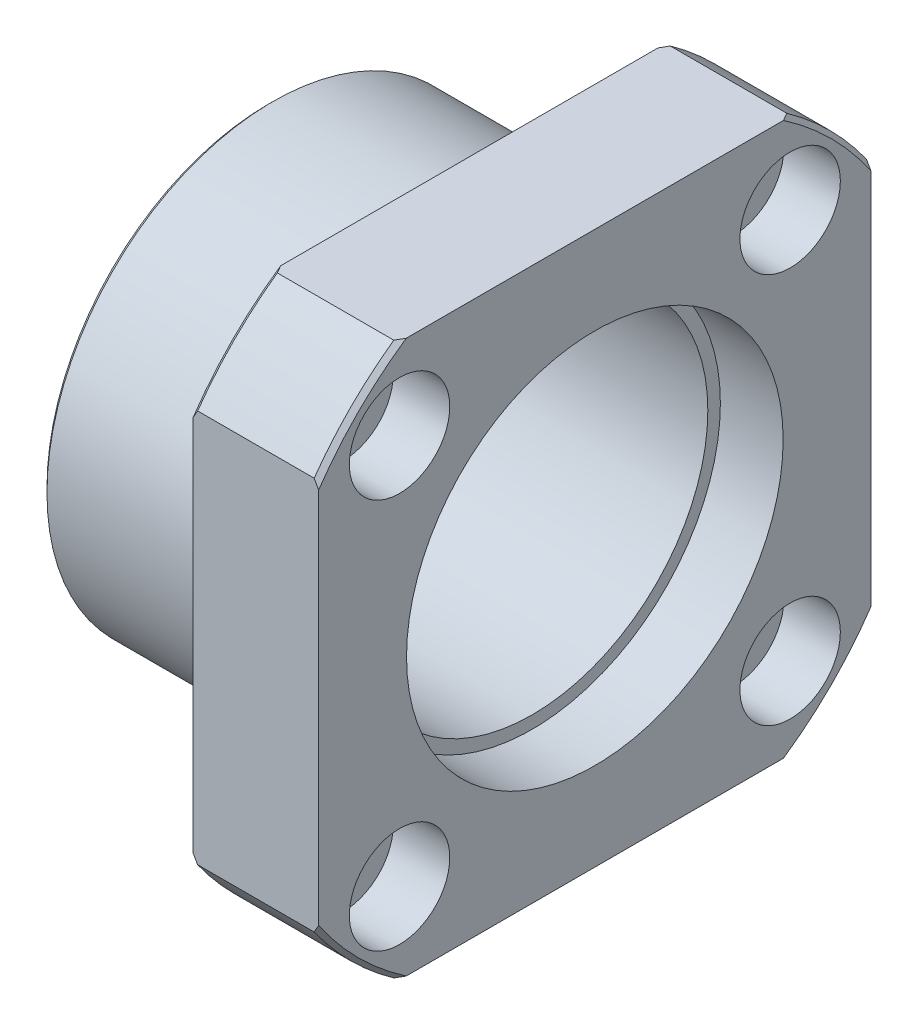
SolidWorks part; units mm, degrees
material "Alloy Steel (SS)"
ref_plane "Front Plane" through (0, 0, 0) normal (0, 0, 1) x (1, 0, 0)
ref_plane "Top Plane" through (0, 0, 0) normal (0, 1, 0) x (1, 0, 0)
ref_plane "Right Plane" through (0, 0, 0) normal (1, 0, 0) x (0, 0, -1)
ref_plane "Plane1" through (16, 0, 0) normal (-1, 0, 0) x (0, -1, 0)
sketch "Sketch1" plane through (16, 0, 0) normal (-1, 0, 0) x (0, -1, 0)
  line L0 (15.6525, 22) -> (-15.6525, 22)
  line L1 (-22, 15.6525) -> (-22, -15.6525)
  line L2 (-15.6525, -22) -> (15.6525, -22)
  line L3 (22, -15.6525) -> (22, 15.6525)
  arc A0 (-15.6525, 22) -> (-22, 15.6525) centre (0, 0) ccw
  arc A1 (-22, -15.6525) -> (-15.6525, -22) centre (0, 0) ccw
  arc A2 (15.6525, -22) -> (22, -15.6525) centre (0, 0) ccw
  arc A3 (22, 15.6525) -> (15.6525, 22) centre (0, 0) ccw
extrude "Boss-Extrude1" add sketch "Sketch1" against normal blind 10
sketch "Sketch2" plane through (0, 0, 0) normal (0, 0, 1) x (1, 0, 0)
  line L0 (0, 18) -> (0, 0)
  line L1 (0, 0) -> (16, 0)
  line L2 (16, 0) -> (16, 18)
  line L3 (16, 18) -> (0, 18)
  line L4 (0, 0) -> (16, 0) construction
revolve "Revolve1" add sketch "Sketch2" angle 360 about L4
sketch "Sketch3" plane through (0, 0, 0) normal (0, 0, 1) x (1, 0, 0)
  line L0 (0, 7.75) -> (0, 0)
  line L1 (0, 0) -> (26, 0)
  line L2 (26, 0) -> (26, 15)
  line L3 (26, 15) -> (21, 15)
  line L4 (21, 15) -> (21, 14)
  line L5 (21, 14) -> (5, 14)
  line L6 (5, 14) -> (5, 7.75)
  line L7 (5, 7.75) -> (0, 7.75)
  line L8 (0, 0) -> (26, 0) construction
revolve "Cut-Revolve1" cut sketch "Sketch3" angle 360 about L8
hole_wizard "CBORE for M4 Hex Head Machine Screw1" positions "Sketch5" profile "Sketch4" counterbore size "M4" standard "ANSI Metric"
sketch "Sketch5" plane through (26, 0, 0) normal (1, 0, 0) x (0, 0, -1)
  point P0 (-15.5563, -15.5563)
  point P1 (15.5563, 15.5563)
  point P2 (15.5563, -15.5563)
  point P3 (-15.5563, 15.5563)
sketch "Sketch4" plane through (26, -15.5563, 15.5563) normal (0, 1, 0) x (0, 0, -1)
  line L0 (0, 0) -> (0, 26)
  line L1 (0, 26) -> (2.25, 26)
  line L3 (2.25, 26) -> (2.25, 4.5)
  line L4 (2.25, 4.5) -> (4, 4.5)
  line L5 (4, 4.5) -> (4, 0)
  line L7 (4, 0) -> (0, 0)
  line L11 (0, -6.35) -> (0, 107.95) construction
  dimension "Thru Hole Dia." = 4.5
  dimension "Thru Hole Depth" = 26
  dimension "C'Bore Dia." = 8
  dimension "C'Bore Depth" = 4.5
chamfer "Chamfer1" distance 0.36 angle 45 9 edges at (26, 19.0919, 19.0919) (26, -19.0919, -19.0919) (16, -19.0919, 19.0919) (26, -19.0919, 19.0919) (16, 19.0919, 19.0919) (26, 19.0919, -19.0919) (16, -19.0919, -19.0919) (0, 0, -18) (16, 19.0919, -19.0919)
fillet "Fillet1" radius 0.3 1 edges at (16, 0, 18)
